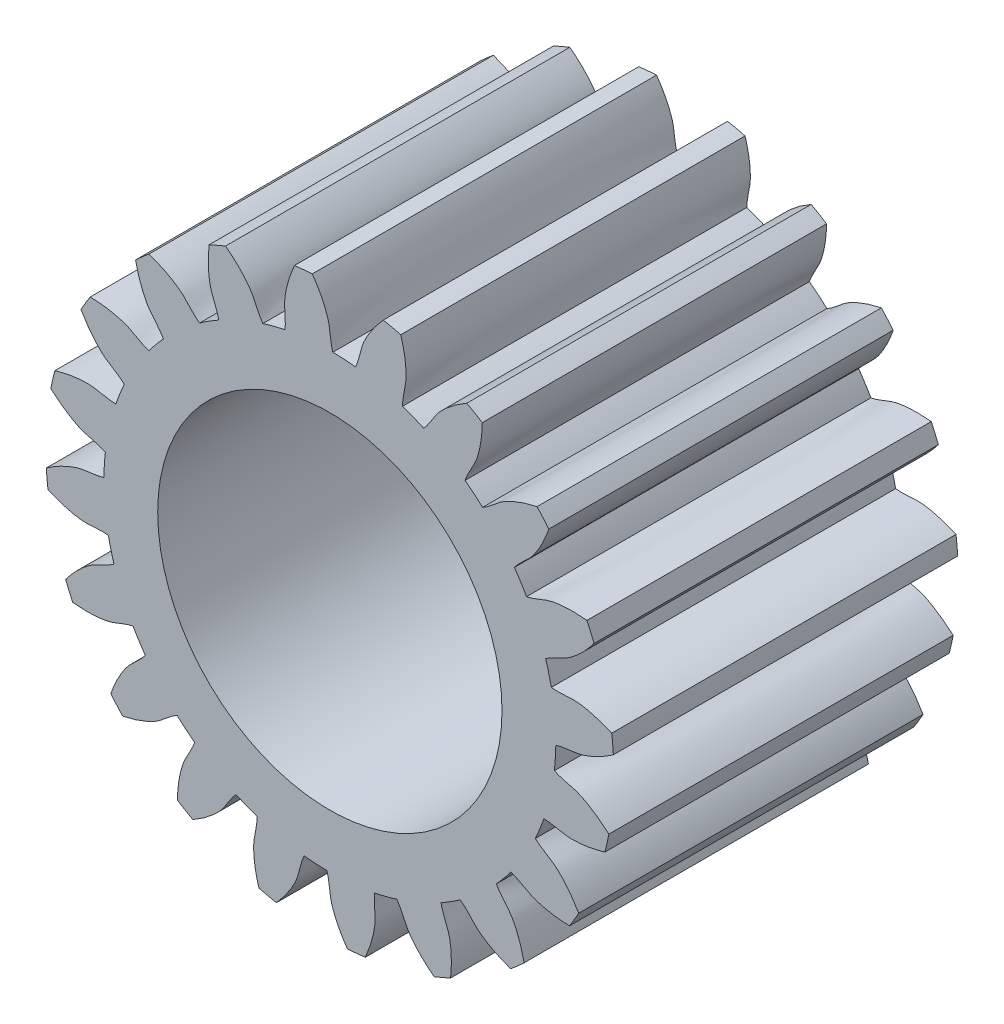
SolidWorks part; units mm, degrees
ref_plane "前视基准面" through (0, 0, 0) normal (0, 0, 1) x (1, 0, 0)
ref_plane "上视基准面" through (0, 0, 0) normal (0, 1, 0) x (1, 0, 0)
ref_plane "右视基准面" through (0, 0, 0) normal (1, 0, 0) x (0, 0, -1)
sketch "草图1" plane through (0, 0, 0) normal (0, 0, 1) x (1, 0, 0)
  circle A0 centre (0, 0) radius 13.125
  circle A1 centre (0, 0) radius 10
extrude "凸台-拉伸1" add sketch "草图1" along normal blind 20
sketch "草图2" plane through (0, 0, 0) normal (0, 0, 1) x (1, 0, 0)
  arc A0 (16.3712, 2.0576) -> (16.4684, 1.02) centre (0, 0) cw
  arc A1 (12.8633, 2.6079) -> (13.1239, -0.1724) centre (0, 0) cw
  spline S0 degree 3 poles (16.4684, 1.02) (16.1694, 0.8125) (15.7083, 0.5303) (15.0632, 0.2415) (14.2739, -0.0393) (13.592, -0.0188) (13.1239, -0.1724) knots 0 0 0 0 0.304015 0.449161 0.589717 1 1 1 1
  spline S1 degree 3 poles (16.3712, 2.0576) (16.0388, 2.2059) (15.5333, 2.3976) (14.8458, 2.5615) (14.018, 2.6908) (13.3518, 2.5439) (12.8633, 2.6079) knots 0 0 0 0 0.304015 0.449161 0.589717 1 1 1 1
extrude "凸台-拉伸2" add sketch "草图2" along normal blind 20
pattern_circular "阵列(圆周)1" count 20 over 360 about axis through (0, 0, 20) along (0, 0, -1) of "凸台-拉伸2"
